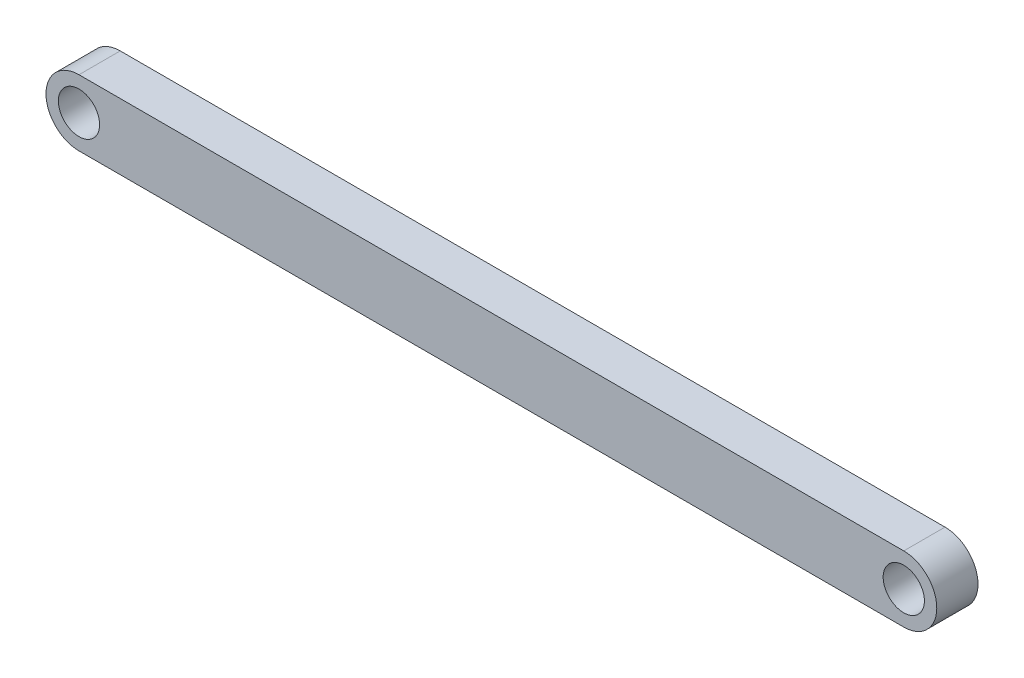
SolidWorks part; units mm, degrees
ref_plane "前视基准面" through (0, 0, 0) normal (0, 0, 1) x (1, 0, 0)
ref_plane "上视基准面" through (0, 0, 0) normal (0, 1, 0) x (1, 0, 0)
ref_plane "右视基准面" through (0, 0, 0) normal (1, 0, 0) x (0, 0, -1)
sketch "草图1" plane through (0, 0, 0) normal (0, 0, 1) x (1, 0, 0)
  line L1 (100, -4) -> (0, -4)
  line L3 (100, 4) -> (0, 4)
  line L5 (50, 4) -> (50, -4) construction
  line L6 (50, 0) -> (0, 0) construction
  arc A0 (0, 4) -> (0, -4) centre (0, 0) ccw
  arc A1 (100, 4) -> (100, -4) centre (100, 0) cw
  circle A2 centre (0, 0) radius 2.5
  circle A3 centre (100, 0) radius 2.5
  point P3 (50, 0)
  dimension "D1" = 8
  dimension "D3" = 5
  dimension "D4" = 5
  dimension "D2" = 100
extrude "凸台-拉伸1" add sketch "草图1" along normal blind 5
